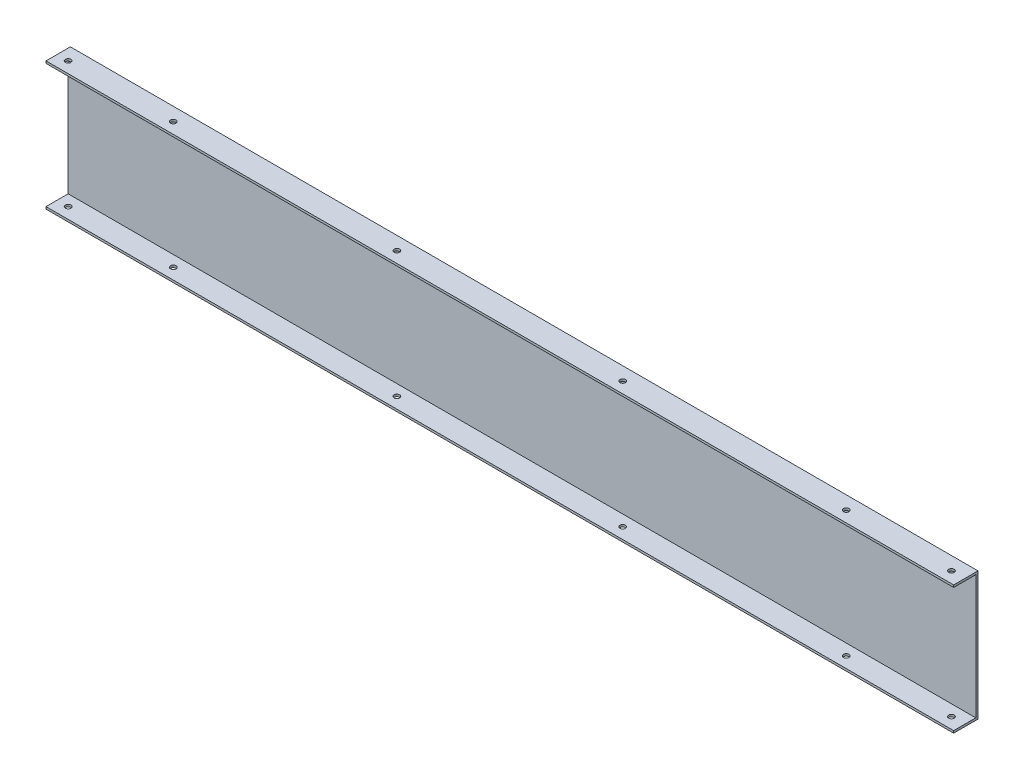
SolidWorks part; units mm, degrees
material "6061 合金"
ref_plane "前视基准面" through (0, 0, 0) normal (0, 0, 1) x (1, 0, 0)
ref_plane "上视基准面" through (0, 0, 0) normal (0, 1, 0) x (1, 0, 0)
ref_plane "右视基准面" through (0, 0, 0) normal (1, 0, 0) x (0, 0, -1)
sketch "草图1" plane through (0, 0, 0) normal (0, 0, 1) x (1, 0, 0)
  line L1 (-14.0782, -7.7887) -> (805.9218, -7.7887)
  line L2 (-14.0782, -7.7887) -> (-14.0782, 108.2113)
  line L3 (-14.0782, 108.2113) -> (805.9218, 108.2113)
  line L4 (805.9218, -7.7887) -> (805.9218, 108.2113)
extrude "凸台-拉伸1" add sketch "草图1" along normal blind 2
sketch "草图2" plane through (0, 0, 2) normal (0, 0, 1) x (1, 0, 0)
  line L0 (805.9218, -7.7887) -> (805.9218, 108.2113) construction
  line L1 (-14.0782, 108.2113) -> (805.9218, 108.2113)
  line L2 (-14.0782, 108.2113) -> (-14.0782, 106.2113)
  line L3 (-14.0782, 106.2113) -> (805.9218, 106.2113)
  line L4 (805.9218, 108.2113) -> (805.9218, 106.2113)
  line L6 (-14.0782, -7.7887) -> (805.9218, -7.7887)
  line L7 (-14.0782, -7.7887) -> (-14.0782, -5.7887)
  line L8 (-14.0782, -5.7887) -> (805.9218, -5.7887)
  line L9 (805.9218, -7.7887) -> (805.9218, -5.7887)
extrude "凸台-拉伸2" add sketch "草图2" along normal blind 20
sketch "草图3" plane through (0, 108.2113, 0) normal (0, 1, 0) x (1, 0, 0)
  circle A0 centre (698.9218, -12) radius 2.5
  circle A1 centre (793.9218, -12) radius 2.5
  circle A2 centre (-4.0782, -12) radius 2.5
  circle A3 centre (90.9218, -12) radius 2.5
  circle A4 centre (292.9218, -12) radius 2.5
  circle A5 centre (496.9218, -12) radius 2.5
extrude "切除-拉伸2" cut sketch "草图3" against normal blind 116
